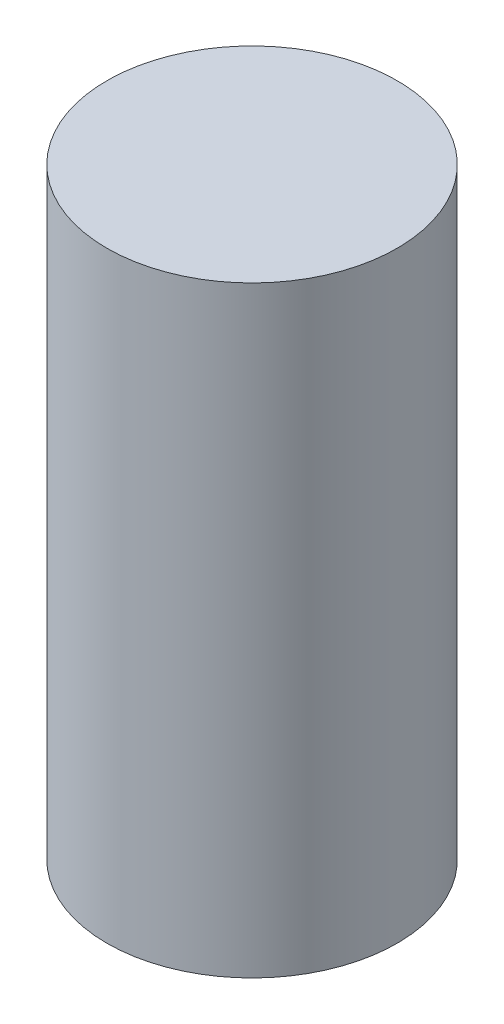
SolidWorks part; units mm, degrees
ref_plane "Front Plane" through (0, 0, 0) normal (0, 0, 1) x (1, 0, 0)
ref_plane "Top Plane" through (0, 0, 0) normal (0, 1, 0) x (1, 0, 0)
ref_plane "Right Plane" through (0, 0, 0) normal (1, 0, 0) x (0, 0, -1)
sketch "Sketch1" plane through (0, 0, 0) normal (0, 1, 0) x (1, 0, 0)
  circle A0 centre (0, 0) radius 3
  dimension "D1" = 6
extrude "Boss-Extrude1" add sketch "Sketch1" along normal blind 12.44
equation "\"bearing_21_OD\"= 21mm"
equation "\"pin_cirlce_diameter\"= 75mm"
equation "\"pin_diam\"= 6mm"
equation "\"gear_thickness\"= 4mm"
equation "\"ball_bearing_diam\"= 2.96mm"
equation "\"bearing_21_outer_clearance\"= 0mm'change this"
equation "\"bearing_15_OD\"= 15mm"
equation "\"bearing_15_outer_clearance\"= 0mm'change this"
equation "\"thrust_bearing_thickness\"= 5mm'measure this irl and change"
equation "\"D1@Boss-Extrude1\"=\"ball_bearing_diam\"*1.50+2*\"gear_thickness\""
